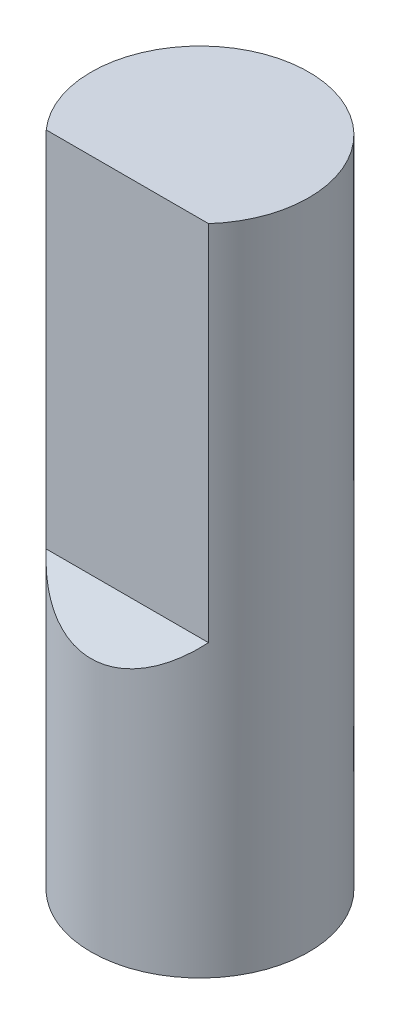
SolidWorks part; units mm, degrees
ref_plane "Front Plane" through (0, 0, 0) normal (0, 0, 1) x (1, 0, 0)
ref_plane "Top Plane" through (0, 0, 0) normal (0, 1, 0) x (1, 0, 0)
ref_plane "Right Plane" through (0, 0, 0) normal (1, 0, 0) x (0, 0, -1)
sketch "Sketch1" plane through (0, 0, 0) normal (0, 1, 0) x (1, 0, 0)
  circle A0 centre (0, 0) radius 3
  dimension "D1" = 6
extrude "Boss-Extrude1" add sketch "Sketch1" along normal blind 18
sketch "Sketch2" plane through (0, 18, 0) normal (0, 1, 0) x (1, 0, 0)
  line L0 (-2.2361, -2) -> (2.2361, -2)
  circle A0 centre (0, 0) radius 3 construction
  circle A2 centre (0, 0) radius 3
  arc A3 (-2.2361, -2) -> (2.2361, -2) centre (0, 0) ccw
  dimension "D2" = 2
  dimension "D1" = 0
extrude "Cut-Extrude1" cut sketch "Sketch2" against normal blind 10
sketch "Sketch3" plane through (0, 0, 0) normal (1, 0, 0) x (0, 0, -1)
  line L0 (-2, 8) -> (-3, 7)
  line L1 (-3, 8) -> (-3, 0) construction
  line L2 (-3, 7) -> (-3, 8)
  line L3 (-3, 8) -> (-2, 8)
extrude "Cut-Extrude2" cut sketch "Sketch3" against normal through all both and the other way through all
